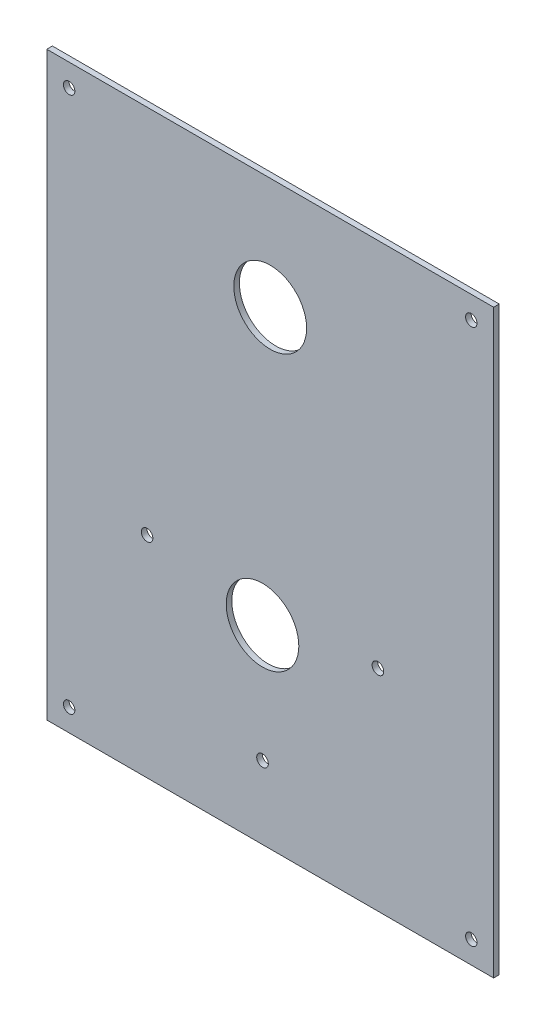
SolidWorks part; units mm, degrees
ref_plane "Front Plane" through (0, 0, 0) normal (0, 0, 1) x (1, 0, 0)
ref_plane "Top Plane" through (0, 0, 0) normal (0, 1, 0) x (1, 0, 0)
ref_plane "Right Plane" through (0, 0, 0) normal (1, 0, 0) x (0, 0, -1)
sketch "Sketch1" plane through (0, 0, 0) normal (0, 0, 1) x (1, 0, 0)
  line L0 (-107.0186, -261.8092) -> (146.9814, -261.8092)
  line L1 (146.9814, -261.8092) -> (146.9814, 68.3908)
  line L2 (146.9814, 68.3908) -> (-107.0186, 68.3908)
  line L3 (-107.0186, 68.3908) -> (-107.0186, -261.8092)
  dimension "D1" = 254
  dimension "D2" = 330.2
extrude "Boss-Extrude1" add sketch "Sketch1" against normal blind 3.175
sketch "Sketch2" plane through (0, 0, 0) normal (0, 0, 1) x (1, 0, 0)
  line L0 (-107.0186, 68.3908) -> (146.9814, 68.3908) construction
  line L1 (146.9814, 68.3908) -> (-107.0186, 68.3908) construction
  line L2 (146.9814, -261.8092) -> (146.9814, 68.3908) construction
  line L3 (19.9814, 68.3908) -> (19.9814, -261.8092) construction
  line L4 (-107.0186, -261.8092) -> (146.9814, -261.8092) construction
  circle A0 centre (19.9814, 4.8908) radius 20.701
  dimension "D1" = 41.402
  dimension "D2" = 63.5
extrude "Cut-Extrude1" cut sketch "Sketch2" against normal through all
sketch "Sketch3" plane through (0, 0, 0) normal (0, 0, 1) x (1, 0, 0)
  line L0 (-107.0186, 68.3908) -> (-107.0186, -261.8092) construction
  line L1 (-50.0074, -142.2296) -> (15.6054, -153.7989) construction
  line L2 (-107.0186, -261.8092) -> (146.9814, -261.8092) construction
  line L3 (146.9814, -261.8092) -> (146.9814, 68.3908) construction
  line L4 (146.9814, 68.3908) -> (-107.0186, 68.3908) construction
  circle A0 centre (-50.0074, -142.2296) radius 3.3
  circle A1 centre (81.2182, -142.2296) radius 3.3
  circle A2 centre (15.6054, -220.4239) radius 3.3
  circle A3 centre (15.6054, -153.7989) radius 20.6375
  circle A4 centre (134.2814, 55.6908) radius 3.2512
  circle A5 centre (-94.3186, 55.6908) radius 3.2512
  circle A6 centre (134.2814, -249.1092) radius 3.2512
  circle A7 centre (-94.3186, -249.1092) radius 3.2512
  point P27 (0, 0)
  point P28 (0, 0)
  point P29 (0, 0)
  point P30 (0, 0)
  dimension "D1" = 6.6
  dimension "D2" = 6.6
  dimension "D3" = 6.6
  dimension "D4" = 41.275
  dimension "D9" = 6.5024
  dimension "D10" = 6.5024
  dimension "D11" = 6.5024
  dimension "D12" = 6.5024
  dimension "D5" = 122.624
  dimension "D6" = 108.0103
  dimension "D7" = 12.7
  dimension "D8" = 12.7
  dimension "D13" = 12.7
  dimension "D14" = 12.7
extrude "Cut-Extrude2" cut sketch "Sketch3" against normal through all
